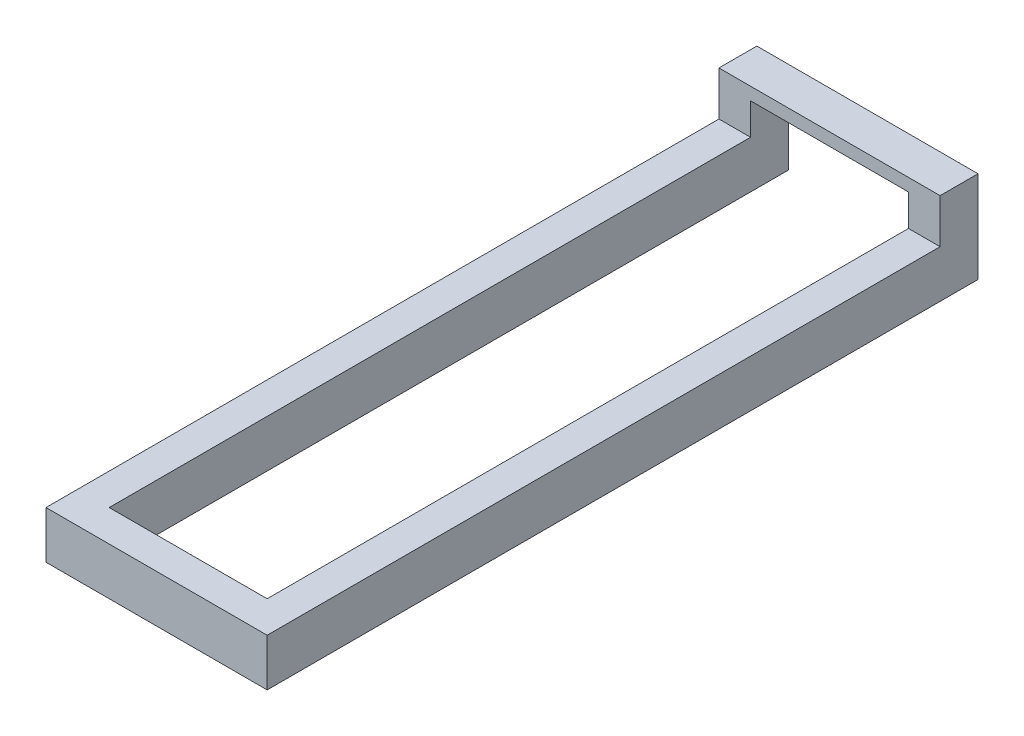
SolidWorks part; units mm, degrees
ref_plane "Front Plane" through (0, 0, 0) normal (0, 0, 1) x (1, 0, 0)
ref_plane "Top Plane" through (0, 0, 0) normal (0, 1, 0) x (1, 0, 0)
ref_plane "Right Plane" through (0, 0, 0) normal (1, 0, 0) x (0, 0, -1)
sketch "Sketch1" plane through (0, 0, 0) normal (0, 1, 0) x (1, 0, 0)
  line L0 (25, 107.5) -> (35, 107.5)
  line L2 (-25, 107.5) -> (-25, -107.5)
  line L3 (-25, -107.5) -> (25, -107.5)
  line L4 (25, 107.5) -> (25, -107.5)
  line L5 (-25, 107.5) -> (25, -107.5) construction
  line L6 (-25, -107.5) -> (25, 107.5) construction
  line L7 (35, 107.5) -> (35, -117.5)
  line L8 (35, -117.5) -> (-35, -117.5)
  line L9 (-35, -117.5) -> (-35, 107.5)
  line L10 (-35, 107.5) -> (-25, 107.5)
  point P0 (0, 0)
  dimension "D1" = 50
  dimension "D2" = 215
  dimension "D3" = 50
  dimension "D4" = 10
  dimension "D5" = 10
  dimension "D6" = 10
extrude "Boss-Extrude1" add sketch "Sketch1" along normal mid plane 15
sketch "Sketch2" plane through (0, 0, -107.5) normal (0, 0, -1) x (-1, 0, 0)
  line L1 (-35, 7.5) -> (-25, 7.5)
  line L2 (-35, 7.5) -> (-35, 17.5)
  line L3 (-35, 17.5) -> (-25, 17.5)
  line L4 (-25, 7.5) -> (-25, 17.5)
  line L5 (25, 7.5) -> (35, 7.5)
  line L6 (25, 7.5) -> (25, 17.5)
  line L7 (25, 17.5) -> (35, 17.5)
  line L8 (35, 7.5) -> (35, 17.5)
  line L9 (-35, 17.5) -> (35, 17.5)
  line L10 (-35, 17.5) -> (-35, 21.5)
  line L11 (-35, 21.5) -> (35, 21.5)
  line L12 (35, 17.5) -> (35, 21.5)
  line M7 (-25, 7.5) -> (-35, 7.5)
  dimension "D1" = 10
  dimension "D2" = 4
  dimension "D3" = 70
  dimension "D4" = 10
extrude "Boss-Extrude2" add sketch "Sketch2" against normal blind 12 contours L4 L3 L2 M7 | L7 L12 L11 L10 L3 L9 | L5 L8 L7 L6
